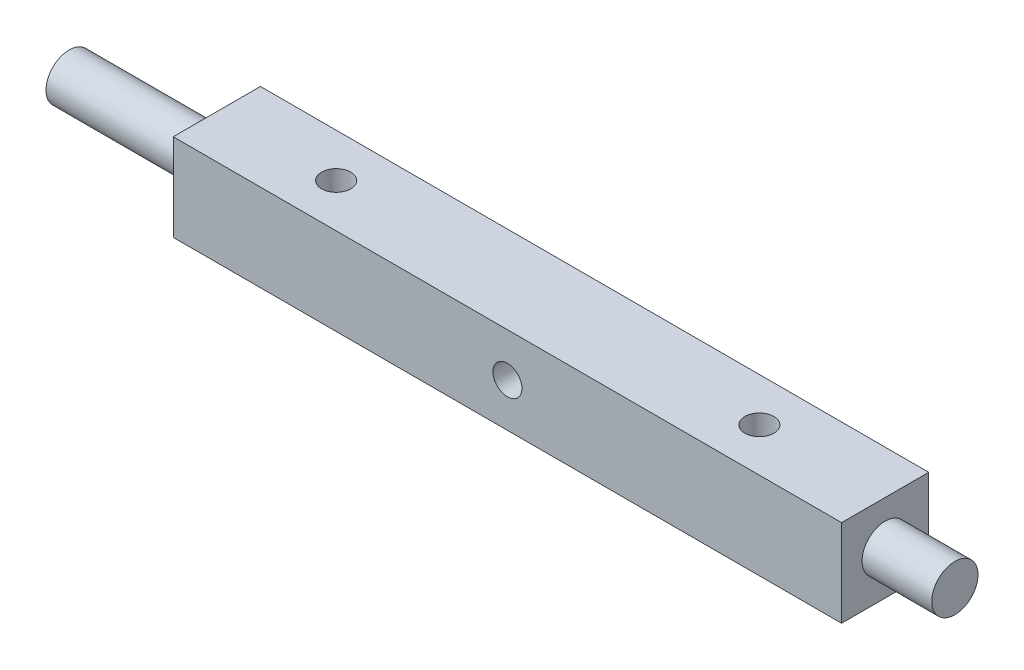
SolidWorks part; units mm, degrees
material "Fundición gris (SN)"
ref_plane "Alzado" through (0, 0, 0) normal (0, 0, 1) x (1, 0, 0)
ref_plane "Planta" through (0, 0, 0) normal (0, 1, 0) x (1, 0, 0)
ref_plane "Vista lateral" through (0, 0, 0) normal (1, 0, 0) x (0, 0, -1)
sketch "Croquis1" plane through (0, 0, 0) normal (1, 0, 0) x (0, 0, -1)
  line L1 (7.5, -7.5) -> (-7.5, -7.5)
  line L2 (7.5, -7.5) -> (7.5, 7.5)
  line L3 (7.5, 7.5) -> (-7.5, 7.5)
  line L4 (-7.5, -7.5) -> (-7.5, 7.5)
  line L5 (7.5, -7.5) -> (-7.5, 7.5) construction
  line L6 (7.5, 7.5) -> (-7.5, -7.5) construction
  point P0 (0, 0)
  dimension "D1" = 15
  dimension "D2" = 15
extrude "Saliente-Extruir1" add sketch "Croquis1" along normal mid plane 115
sketch "Croquis2" plane through (0, 0, 7.5) normal (0, 0, 1) x (1, 0, 0)
  circle A0 centre (0, 0) radius 2.5
  dimension "D1" = 5
extrude "Cortar-Extruir1" cut sketch "Croquis2" against normal through all
sketch "Croquis3" plane through (0, 7.5, 0) normal (0, 1, 0) x (1, 0, 0)
  line L0 (-57.5, 0) -> (57.5, 0) construction
  line L1 (-57.5, 7.5) -> (-57.5, -7.5) construction
  line L2 (57.5, 7.5) -> (57.5, -7.5) construction
  circle A0 centre (-36.9743, 0) radius 2.5
  circle A1 centre (35.8563, 0) radius 2.5
  dimension "D1" = 5
  dimension "D2" = 5
extrude "Cortar-Extruir2" cut sketch "Croquis3" against normal through all
sketch "Croquis4" plane through (-57.5, 0, 0) normal (-1, 0, 0) x (0, 0, 1)
  circle A0 centre (0, 0) radius 4
  dimension "D1" = 8
extrude "Saliente-Extruir2" add sketch "Croquis4" along normal blind 25.4
sketch "Croquis5" plane through (57.5, 0, 0) normal (1, 0, 0) x (0, 0, -1)
  circle A0 centre (0, 0) radius 3.9766
extrude "Saliente-Extruir3" add sketch "Croquis5" along normal blind 12
